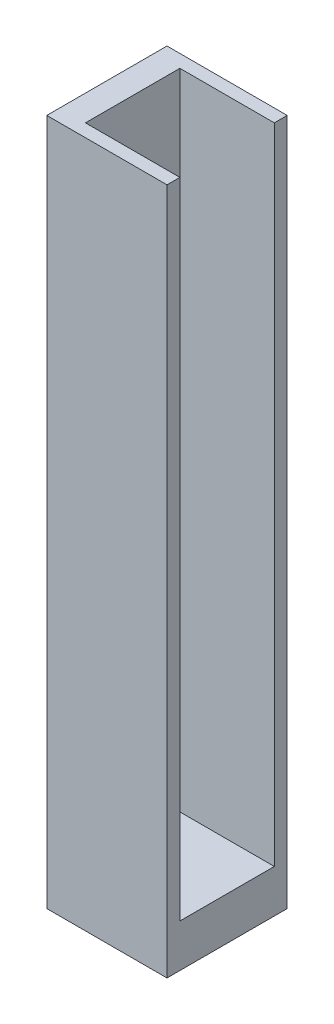
SolidWorks part; units mm, degrees
ref_plane "Plan de face" through (0, 0, 0) normal (0, 0, 1) x (1, 0, 0)
ref_plane "Plan de dessus" through (0, 0, 0) normal (0, 1, 0) x (1, 0, 0)
ref_plane "Plan de droite" through (0, 0, 0) normal (1, 0, 0) x (0, 0, -1)
sketch "Esquisse1" plane through (0, 0, 0) normal (0, 1, 0) x (1, 0, 0)
  line L1 (-54.753, 42.1271) -> (-40.753, 42.1271)
  line L2 (-54.753, 42.1271) -> (-54.753, 56.1271)
  line L3 (-54.753, 56.1271) -> (-40.753, 56.1271)
  line L4 (-40.753, 42.1271) -> (-40.753, 56.1271)
  dimension "D1" = 14
  dimension "D2" = 14
extrude "Boss.-Extru.1" add sketch "Esquisse1" along normal blind 80
sketch "Esquisse2" plane through (0, 80, 0) normal (0, 1, 0) x (1, 0, 0)
  line L1 (-51.753, 43.6271) -> (-40.753, 43.6271)
  line L2 (-51.753, 43.6271) -> (-51.753, 54.6271)
  line L3 (-51.753, 54.6271) -> (-40.753, 54.6271)
  line L4 (-40.753, 43.6271) -> (-40.753, 54.6271)
  line L5 (-51.753, 43.6271) -> (-40.753, 54.6271) construction
  line L6 (-51.753, 54.6271) -> (-40.753, 43.6271) construction
  point P0 (-46.253, 49.1271)
  dimension "D1" = 11
  dimension "D2" = 11
  dimension "D3" = 3
  dimension "D4" = 1.5
extrude "Enlèv. mat.-Extru.1" cut sketch "Esquisse2" against normal blind 75
